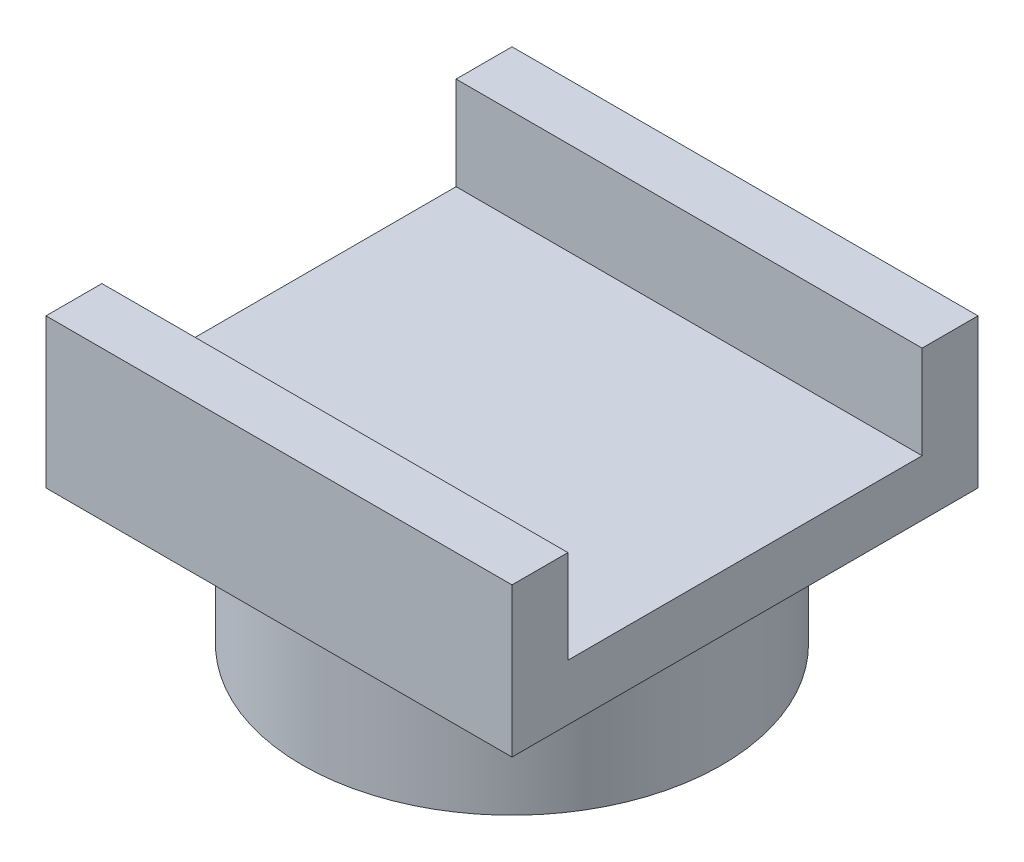
SolidWorks part; units mm, degrees
ref_plane "Plan de face" through (0, 0, 0) normal (0, 0, 1) x (1, 0, 0)
ref_plane "Plan de dessus" through (0, 0, 0) normal (0, 1, 0) x (1, 0, 0)
ref_plane "Plan de droite" through (0, 0, 0) normal (1, 0, 0) x (0, 0, -1)
sketch "Esquisse1" plane through (0, 0, 0) normal (0, 1, 0) x (1, 0, 0)
  circle A0 centre (0, 0) radius 4.5
  dimension "D1" = 9
extrude "Boss.-Extru.1" add sketch "Esquisse1" along normal blind 2.9
sketch "Esquisse2" plane through (0, 2.9, 0) normal (0, 1, 0) x (1, 0, 0)
  line L1 (-5, -5) -> (5, -5)
  line L2 (-5, -5) -> (-5, 5)
  line L3 (-5, 5) -> (5, 5)
  line L4 (5, -5) -> (5, 5)
  line L5 (-5, -5) -> (5, 5) construction
  line L6 (-5, 5) -> (5, -5) construction
  point P0 (0, 0)
  dimension "D1" = 10
  dimension "D2" = 10
extrude "Boss.-Extru.2" add sketch "Esquisse2" along normal blind 1.2
sketch "Esquisse3" plane through (0, 4.1, 0) normal (0, 1, 0) x (1, 0, 0)
  line L0 (5, -5) -> (5, 5) construction
  line L1 (-5, 5) -> (5, 5)
  line L2 (-5, 5) -> (-5, 3.8)
  line L3 (-5, 3.8) -> (5, 3.8)
  line L4 (5, 5) -> (5, 3.8)
  line L6 (-5, -5) -> (5, -5)
  line L7 (-5, -5) -> (-5, -3.8)
  line L8 (-5, -3.8) -> (5, -3.8)
  line L9 (5, -5) -> (5, -3.8)
  dimension "D1" = 1.2
  dimension "D2" = 1.2
extrude "Boss.-Extru.3" add sketch "Esquisse3" along normal blind 2
